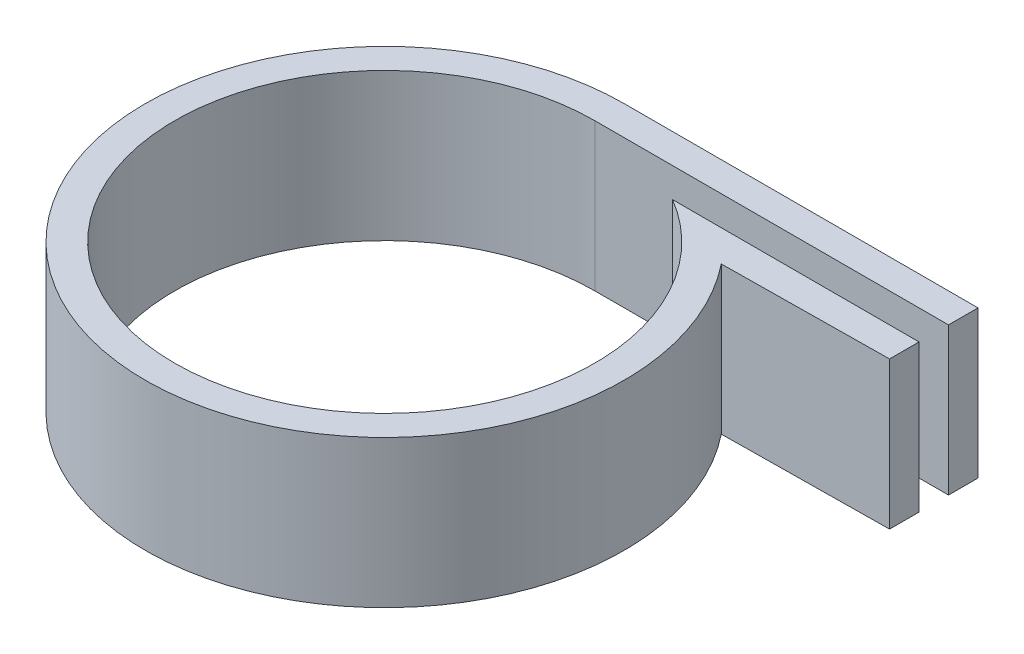
SolidWorks part; units mm, degrees
ref_plane "Front Plane" through (0, 0, 0) normal (0, 0, 1) x (1, 0, 0)
ref_plane "Top Plane" through (0, 0, 0) normal (0, 1, 0) x (1, 0, 0)
ref_plane "Right Plane" through (0, 0, 0) normal (1, 0, 0) x (0, 0, -1)
sketch "Sketch1" plane through (0, 0, 0) normal (0, 1, 0) x (1, 0, 0)
  line L0 (7.2801, 12.25) -> (24, 12.25)
  line L1 (0, 16.25) -> (24, 16.25)
  line L3 (0, 14.25) -> (24, 14.25)
  line L4 (24, 16.25) -> (24, 14.25)
  line L5 (24, 12.25) -> (24, 10.25)
  line L6 (24, 10.25) -> (12.7121, 10.1226)
  arc A0 (0, 14.25) -> (7.2801, 12.25) centre (0, 0) ccw
  arc A1 (0, 16.25) -> (12.7121, 10.1226) centre (0, 0) ccw
  dimension "D1" = 28.5
  dimension "D2" = 2
  dimension "D3" = 2
  dimension "D4" = 24
  dimension "D5" = 2
  dimension "D6" = 2
extrude "Boss-Extrude1" add sketch "Sketch1" along normal blind 10
